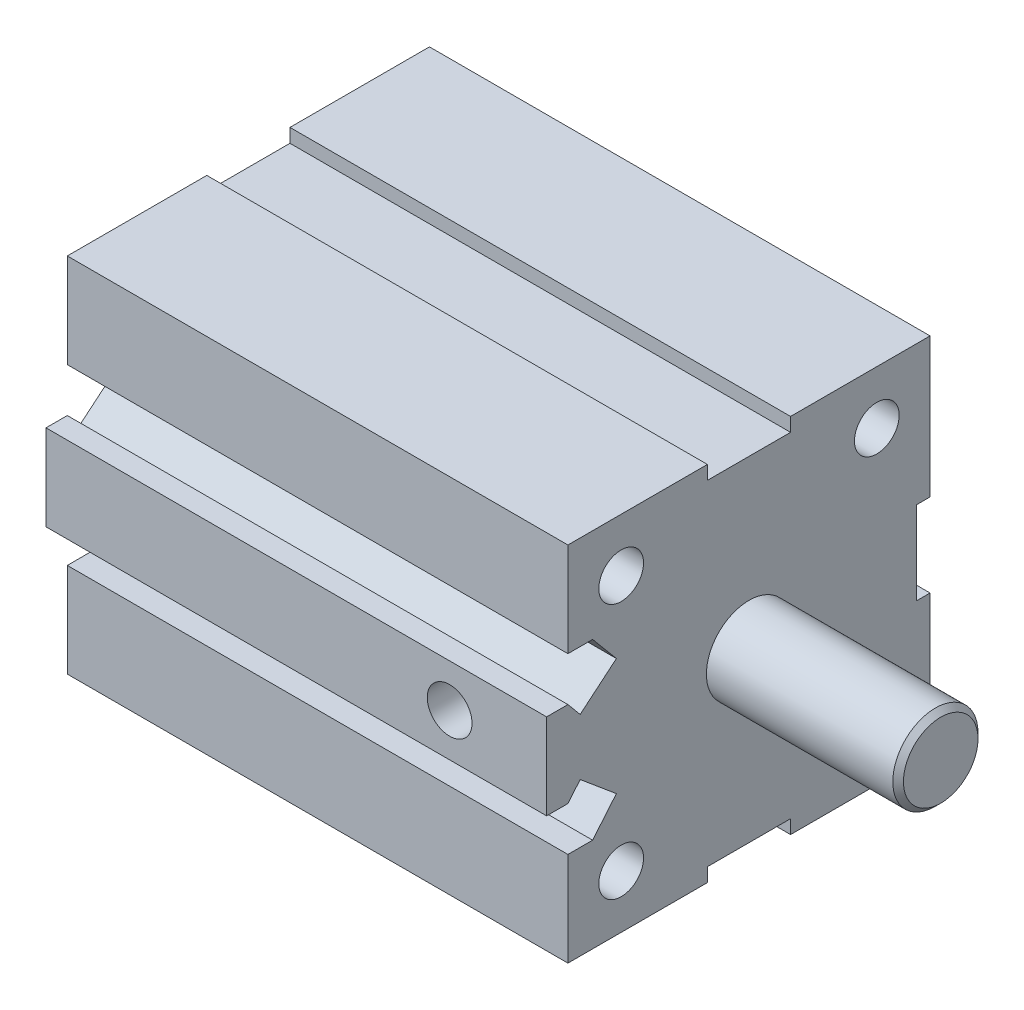
SolidWorks part; units mm, degrees
ref_plane "前视基准面" through (0, 0, 0) normal (0, 0, 1) x (1, 0, 0)
ref_plane "上视基准面" through (0, 0, 0) normal (0, 1, 0) x (1, 0, 0)
ref_plane "右视基准面" through (0, 0, 0) normal (1, 0, 0) x (0, 0, -1)
sketch "草图1" plane through (0, 0, 0) normal (1, 0, 0) x (0, 0, -1)
  line L0 (0, 0) -> (0, 57.5966) construction
  line L1 (-17, 17) -> (17, 17)
  line L2 (-17, 17) -> (-17, -17)
  line L3 (-17, -17) -> (17, -17)
  line L4 (17, 17) -> (17, -17)
  line L5 (0, 0) -> (72.7248, 0) construction
  dimension "D1" = 34
extrude "凸台-拉伸1" add sketch "草图1" along normal mid plane 47
sketch "草图2" plane through (23.5, 0, 0) normal (1, 0, 0) x (0, 0, -1)
  line L0 (17, 17) -> (-17, 17) construction
  line L1 (-3.9037, 17) -> (3.9037, 17)
  line L2 (-3.9037, 17) -> (-3.9037, 15.7066)
  line L3 (-3.9037, 15.7066) -> (3.9037, 15.7066)
  line L4 (3.9037, 17) -> (3.9037, 15.7066)
  line L5 (0, 0) -> (0, 24.0651) construction
  line L6 (0, 0) -> (17, 17) construction
  line L7 (0, 0) -> (19.7972, 0) construction
  line L8 (-3.9037, -17) -> (-3.9037, -15.7066)
  line L9 (3.9037, -17) -> (3.9037, -15.7066)
  line L10 (-3.9037, -15.7066) -> (3.9037, -15.7066)
  line L11 (-3.9037, -17) -> (3.9037, -17)
  line L12 (17, -3.9037) -> (15.7066, -3.9037)
  line L13 (17, 3.9037) -> (15.7066, 3.9037)
  line L14 (15.7066, -3.9037) -> (15.7066, 3.9037)
  line L15 (17, -3.9037) -> (17, 3.9037)
extrude "切除-拉伸1" cut sketch "草图2" against normal through all
sketch "草图3" plane through (23.5, 0, 0) normal (1, 0, 0) x (0, 0, -1)
  line L0 (-17, 8.1609) -> (-14.6819, 8.1609)
  line L1 (-17, 17) -> (-17, -17) construction
  line L2 (-14.6819, 8.1609) -> (-12.4494, 5.4909)
  line L3 (-12.4494, 5.4909) -> (-15.8492, 2.6482)
  line L4 (-15.8492, 2.6482) -> (-17, 4.0245)
  line L5 (-17, 4.0245) -> (-17, 8.1609)
  line L6 (0, 0) -> (-27.0733, 0) construction
  line L7 (-17, -4.0245) -> (-17, -8.1609)
  line L8 (-15.8492, -2.6482) -> (-17, -4.0245)
  line L9 (-12.4494, -5.4909) -> (-15.8492, -2.6482)
  line L10 (-14.6819, -8.1609) -> (-12.4494, -5.4909)
  line L11 (-17, -8.1609) -> (-14.6819, -8.1609)
extrude "切除-拉伸2" cut sketch "草图3" against normal through all
sketch "草图4" plane through (23.5, 0, 0) normal (1, 0, 0) x (0, 0, -1)
  line L1 (-17, 4.0245) -> (-19, 4.0245)
  line L2 (-17, 4.0245) -> (-17, -4.0245)
  line L3 (-17, -4.0245) -> (-19, -4.0245)
  line L4 (-19, 4.0245) -> (-19, -4.0245)
  line L5 (17, 3.9037) -> (17, 17) construction
  dimension "D1" = 36
extrude "凸台-拉伸2" add sketch "草图4" against normal up to surface (47 mm away) up to face at (-23.5, 0, 3.4057)
hole_wizard "M5x0.8 螺纹孔1" positions "草图6" profile "草图5" tap size "M5x0.8" standard "JIS"
sketch "草图6" plane through (0, 0, 19) normal (0, 0, 1) x (1, 0, 0)
  point P1 (14.3966, 0)
sketch "草图5" plane through (14.3966, 0, 19) normal (1, 0, 0) x (0, -1, 0)
  line L0 (0, 0) -> (0, 13.6618)
  line L1 (0, 13.6618) -> (2.1, 12.4)
  line L2 (2.1, 12.4) -> (2.1, 0)
  line L5 (2.1, 0) -> (0, 0)
  line L10 (0, 13.6618) -> (-2.1, 12.4) construction
  line L11 (0, -6.35) -> (0, 107.95) construction
  dimension "螺纹孔钻头直径" = 4.2
  dimension "螺纹孔钻头深度" = 12.4
  dimension "导头角度" = 118
cosmetic thread "孔螺蚊线1" parameters "D1"=10, "D2"=5
sketch "草图7" plane through (23.5, 0, 0) normal (1, 0, 0) x (0, 0, -1)
  circle A0 centre (0, 0) radius 4
  dimension "D1" = 8
extrude "凸台-拉伸3" add sketch "草图7" along normal blind 18
sketch "草图8" plane through (-23.5, 0, 0) normal (-1, 0, 0) x (0, 0, 1)
  circle A0 centre (0, 0) radius 4
  dimension "D1" = 8
extrude "凸台-拉伸4" add sketch "草图8" along normal blind 8
hole_wizard "M4x0.7 螺纹孔1" positions "草图10" profile "草图9" tap size "M4x0.7" standard "JIS"
sketch "草图10" plane through (-31.5, 0, 0) normal (-1, 0, 0) x (0, 0, 1)
  point P1 (0, 0)
sketch "草图9" plane through (-31.5, 0, 0) normal (0, 1, 0) x (0, 0, 1)
  line L0 (0, 0) -> (0, 11.0914)
  line L1 (0, 11.0914) -> (1.65, 10.1)
  line L2 (1.65, 10.1) -> (1.65, 0)
  line L5 (1.65, 0) -> (0, 0)
  line L10 (0, 11.0914) -> (-1.65, 10.1) construction
  line L11 (0, -6.35) -> (0, 107.95) construction
  dimension "螺纹孔钻头直径" = 3.3
  dimension "螺纹孔钻头深度" = 10.1
  dimension "导头角度" = 118
cosmetic thread "孔螺蚊线2" parameters "D1"=8, "D2"=4
hole_wizard "M5x0.8 螺纹孔2" positions "草图12" profile "草图11" tap size "M5x0.8" standard "JIS"
sketch "草图12" plane through (23.5, 0, 0) normal (1, 0, 0) x (0, 0, -1)
  line L0 (0, -20.7201) -> (0, 20.7201) construction
  line L2 (0, 0) -> (12.3791, 0) construction
  point P0 (-12, 12)
  point P9 (12, 12)
  point P16 (12, -12)
  point P17 (-12, -12)
  dimension "D1" = 24
  dimension "D2" = 24
sketch "草图11" plane through (23.5, 12, 12) normal (0, 1, 0) x (0, 0, -1)
  line L0 (0, 0) -> (0, 13.6618)
  line L1 (0, 13.6618) -> (2.1, 12.4)
  line L2 (2.1, 12.4) -> (2.1, 0)
  line L5 (2.1, 0) -> (0, 0)
  line L10 (0, 13.6618) -> (-2.1, 12.4) construction
  line L11 (0, -6.35) -> (0, 107.95) construction
  dimension "螺纹孔钻头直径" = 4.2
  dimension "螺纹孔钻头深度" = 12.4
  dimension "导头角度" = 118
cosmetic thread "孔螺蚊线3" parameters "D1"=10, "D2"=5
cosmetic thread "孔螺蚊线4" parameters "D1"=10, "D2"=5
cosmetic thread "孔螺蚊线5" parameters "D1"=10, "D2"=5
cosmetic thread "孔螺蚊线6" parameters "D1"=10, "D2"=5
chamfer "倒角1" distance 0.5 angle 45 1 edges at (41.5, 0, -4)
